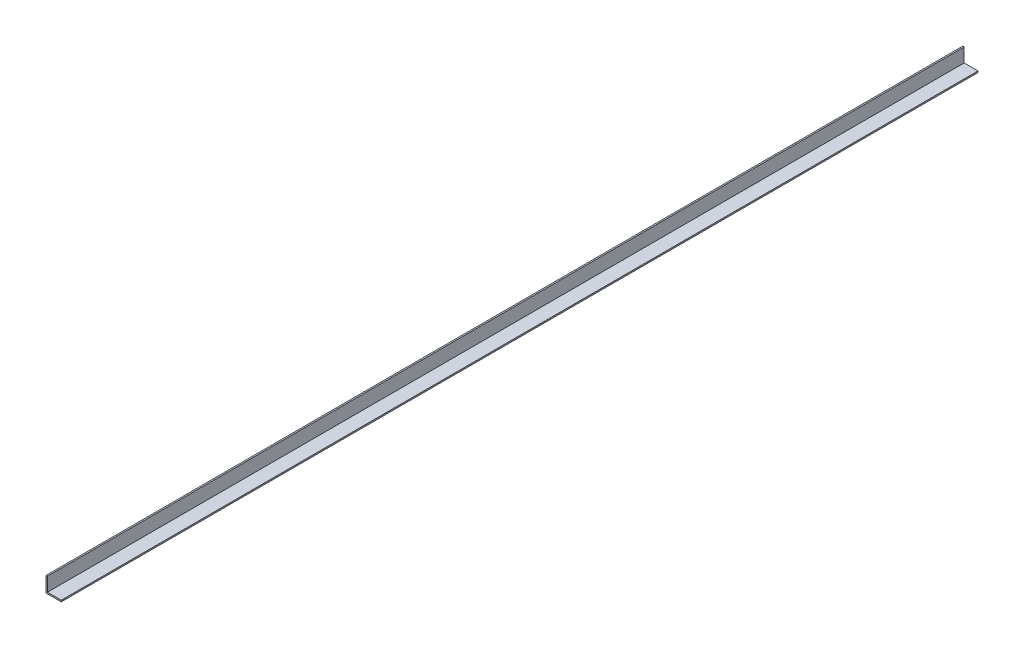
SolidWorks part; units mm, degrees
material "ASTM A36 Acero"
ref_plane "Alzado" through (0, 0, 0) normal (0, 0, 1) x (1, 0, 0)
ref_plane "Planta" through (0, 0, 0) normal (0, 1, 0) x (1, 0, 0)
ref_plane "Vista lateral" through (0, 0, 0) normal (1, 0, 0) x (0, 0, -1)
sketch "Croquis1" plane through (0, 0, 0) normal (0, 0, 1) x (1, 0, 0)
  line L0 (0, 101.6) -> (0, 0)
  line L1 (0, 0) -> (101.6, 0)
  line L2 (101.6, 0) -> (101.6, 9.53)
  line L3 (101.6, 9.53) -> (9.53, 9.53)
  line L4 (9.53, 9.53) -> (9.53, 101.6)
  line L5 (9.53, 101.6) -> (0, 101.6)
  dimension "D1" = 9.53
  dimension "D2" = 101.6
extrude "Saliente-Extruir1" add sketch "Croquis1" against normal blind 6100
